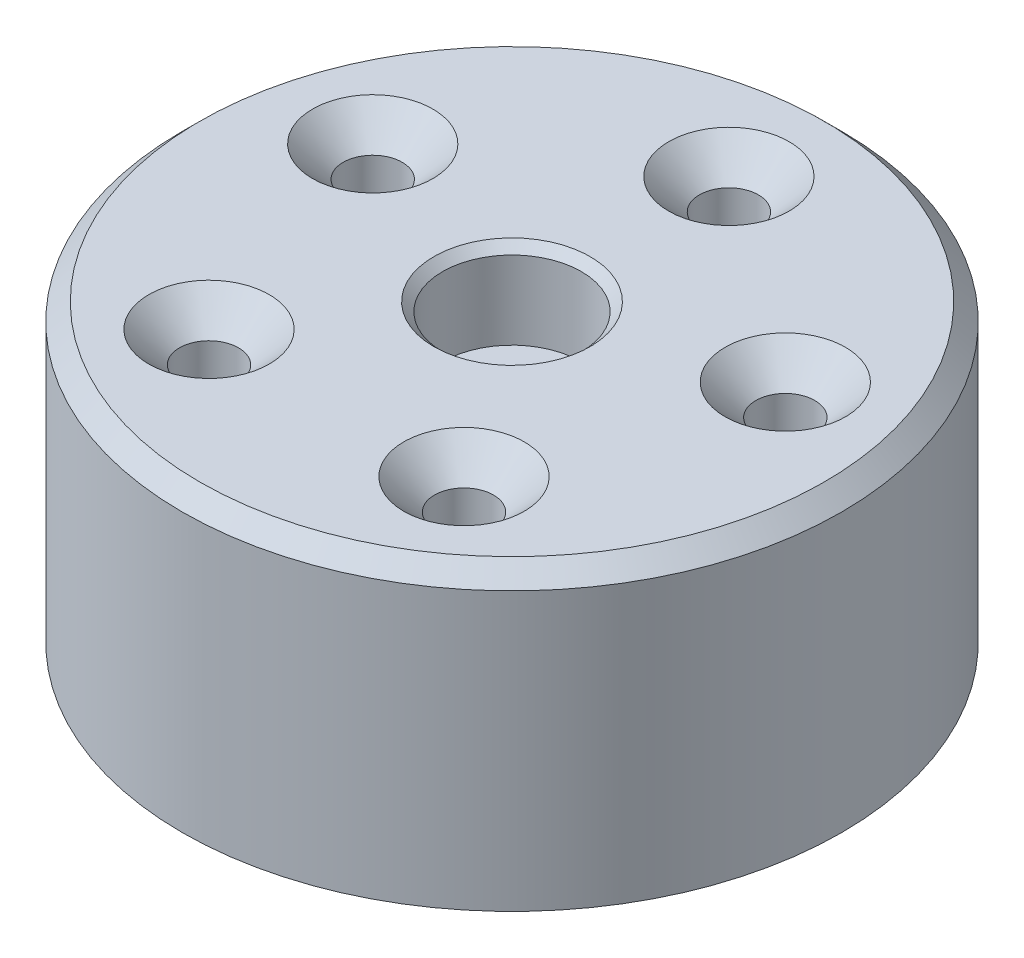
SolidWorks part; units mm, degrees
material "PA Type 6"
ref_plane "Front Plane" through (0, 0, 0) normal (0, 0, 1) x (1, 0, 0)
ref_plane "Top Plane" through (0, 0, 0) normal (0, 1, 0) x (1, 0, 0)
ref_plane "Right Plane" through (0, 0, 0) normal (1, 0, 0) x (0, 0, -1)
sketch "Sketch1" plane through (0, 0, 0) normal (0, 0, 1) x (1, 0, 0)
  line L0 (0, 0) -> (0, 71) construction
  line L7 (17, 0) -> (19, 0)
  line L8 (19, 0) -> (19, 17)
  line L9 (19, 17) -> (4, 17)
  line L10 (4, 17) -> (4, 12)
  line L11 (4, 12) -> (0, 12)
  line L12 (0, 12) -> (0, 2)
  line L13 (0, 2) -> (17, 2)
  line L14 (17, 2) -> (17, 0)
  dimension "D1" = 17
  dimension "D2" = 19
  dimension "D3" = 2
  dimension "D4" = 4
  dimension "D5" = 5
  dimension "D6" = 10
revolve "Revolve1" add sketch "Sketch1" angle 360 about L0
sketch "Sketch4" plane through (0, 17, 0) normal (0, 1, 0) x (1, 0, 0)
  circle A0 centre (0, 0) radius 12.5
  point P5 (0, 12.5)
  point P11 (11.8882, 3.8627)
  point P12 (7.3473, -10.1127)
  point P13 (-7.3473, -10.1127)
  point P14 (-11.8882, 3.8627)
  dimension "D1" = 25
  dimension "D2" = 5
hole_wizard "CSK for M3 Hex Socket Countersunk Head Screw1" positions "Sketch4" profile "Sketch5" countersink size "M3" standard "DIN" end condition through all
sketch "Sketch5" plane through (-11.8882, 17, -3.8627) normal (1, 0, 0) x (0, 0, 1)
  line L0 (0, 0) -> (0, 17)
  line L1 (0, 17) -> (1.7, 17)
  line L2 (1.7, 17) -> (1.7, 1.77)
  line L3 (1.7, 1.77) -> (3.47, 0)
  line L5 (3.47, 0) -> (0, 0)
  line L6 (-1.7, 1.77) -> (-3.47, 0) construction
  line L11 (0, -6.35) -> (0, 107.95) construction
  dimension "Thru Hole Dia." = 3.4
  dimension "Thru Hole Depth" = 17
  dimension "Near C'Sink Dia." = 6.94
  dimension "Near C'Sink Angle" = 90
sketch "Sketch6" plane through (0, 2, 0) normal (0, -1, 0) x (1, 0, 0)
  circle A0 centre (0, 0) radius 7.5
  dimension "D1" = 15
extrude "Cut-Extrude1" cut sketch "Sketch6" against normal blind 5
chamfer "Chamfer1" distance 3 angle 45 1 edges at (0, 7, -7.5)
chamfer "Chamfer2" distance 1 angle 45 1 edges at (0, 17, -19)
chamfer "Chamfer3" distance 0.5 angle 45 1 edges at (0, 17, -4)
